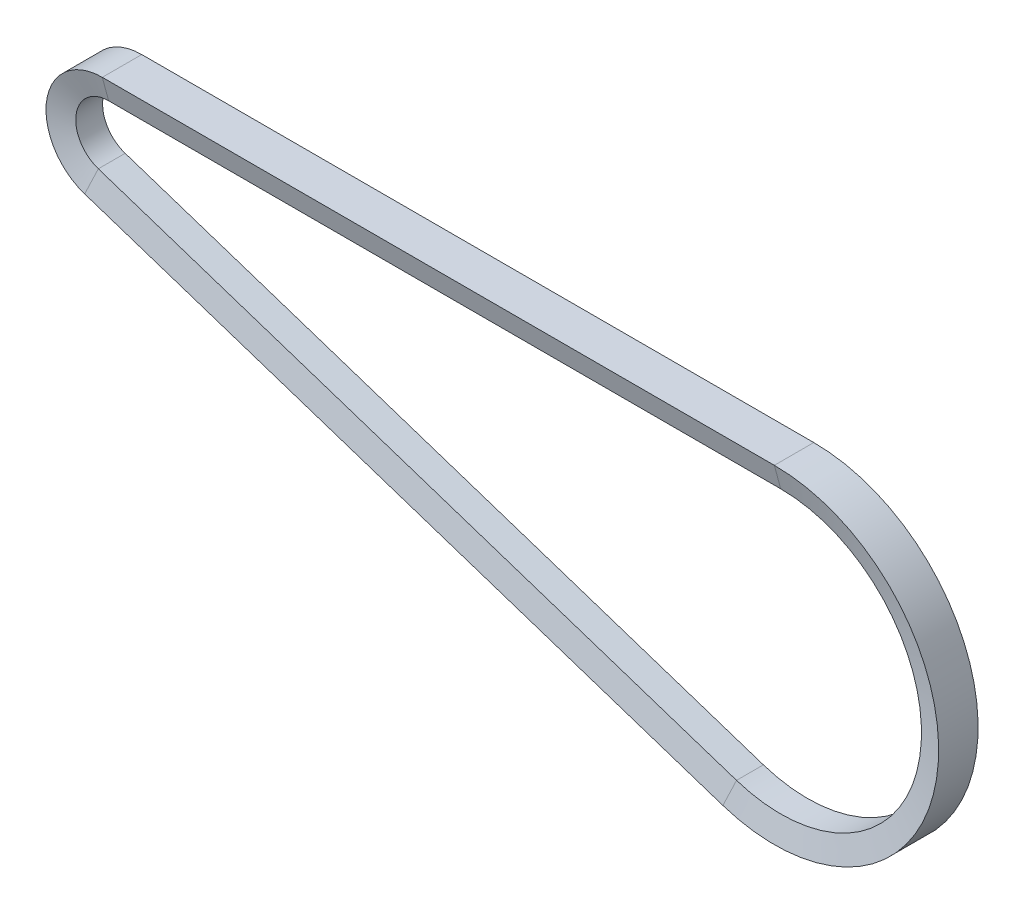
SolidWorks part; units mm, degrees
material "NBR"
ref_plane "Plano frontal" through (0, 0, 0) normal (0, 0, 1) x (1, 0, 0)
ref_plane "Plano superior" through (0, 0, 0) normal (0, 1, 0) x (1, 0, 0)
ref_plane "Plano direito" through (0, 0, 0) normal (1, 0, 0) x (0, 0, -1)
sketch "Esboço1" plane through (0, 0, 0) normal (0, 0, 1) x (1, 0, 0)
  line L0 (0, 0) -> (-140.6642, 0)
  line L1 (-145.0494, -27.2955) -> (126.8707, -116.9807)
  line L2 (145.6642, 0) -> (5, 0)
  arc A0 (-140.6642, 0) -> (-145.0494, -27.2955) centre (-140.6642, -14) ccw
  arc A1 (126.8707, -116.9807) -> (145.6642, 0) centre (145.6642, -60) ccw
  dimension "D1" = 14
  dimension "D2" = 60
  dimension "D3" = 290
  dimension "D4" = 5
sketch "Esboço2" plane through (0, 0, 0) normal (1, 0, 0) x (0, 0, -1)
  line L0 (-8.4, 10) -> (8.4, 10)
  line L1 (8.4, 10) -> (5.7205, 0)
  line L2 (5.7205, 0) -> (-5.7205, 0)
  line L3 (-5.7205, 0) -> (-8.4, 10)
  point P2 (0, 0)
  dimension "D1" = 30
  dimension "D2" = 16.8
  dimension "D3" = 10
sweep "Varredura1" add profiles "Esboço2" path "Esboço1"
sketch "Esboço3" plane through (0, 0, 0) normal (1, 0, 0) x (0, 0, -1)
  line L4 (-8.4, 10) -> (-5.7205, 0)
  line L5 (-5.7205, 0) -> (5.7205, 0)
  line L6 (5.7205, 0) -> (8.4, 10)
  line L7 (8.4, 10) -> (-8.4, 10)
  line L8 (-8.4, 10) -> (-5.7205, 0)
  line L9 (-5.7205, 0) -> (5.7205, 0)
  line L10 (5.7205, 0) -> (8.4, 10)
  line L11 (8.4, 10) -> (-8.4, 10)
  dimension "D1" = 0
extrude "Ressalto-extrusão1" add sketch "Esboço3" along normal up to surface (5 mm away) up to face at (5, 5, 0)
